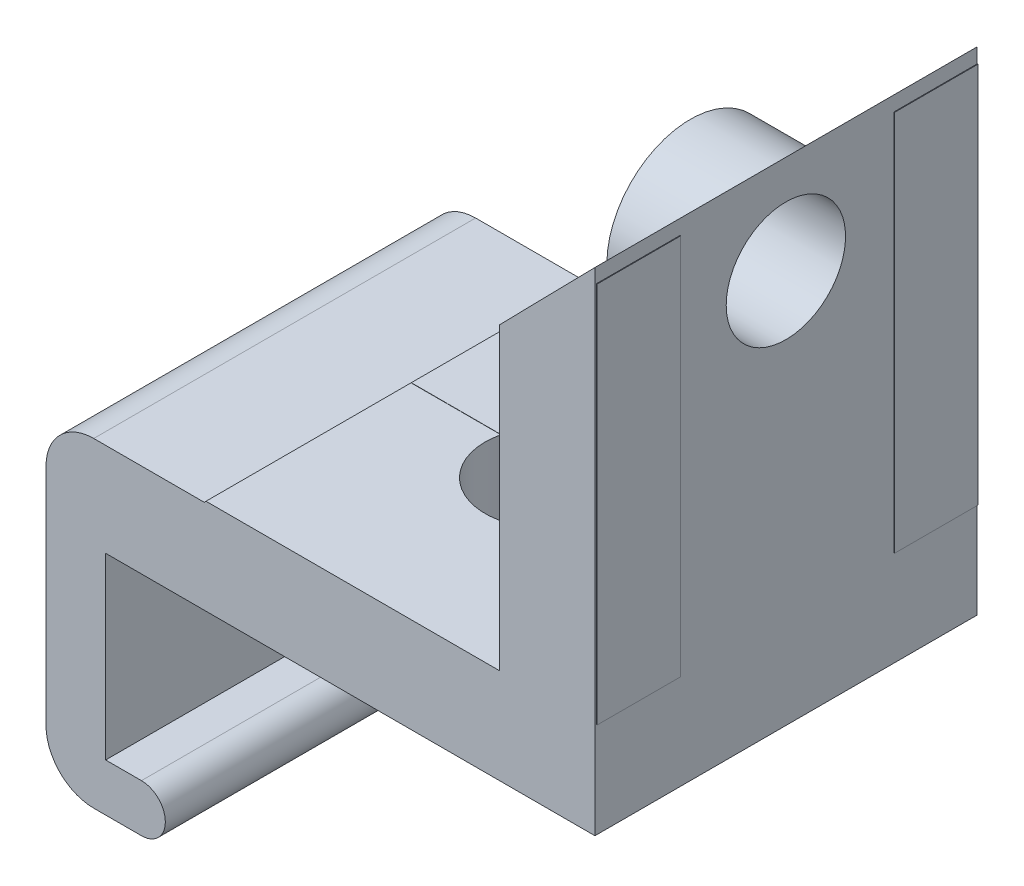
SolidWorks part; units mm, degrees
ref_plane "Front Plane" through (0, 0, 0) normal (0, 0, 1) x (1, 0, 0)
ref_plane "Top Plane" through (0, 0, 0) normal (0, 1, 0) x (1, 0, 0)
ref_plane "Right Plane" through (0, 0, 0) normal (1, 0, 0) x (0, 0, -1)
ref_plane "Plane1" through (16, 0, 0) normal (-1, 0, 0) x (0, -1, 0)
sketch "Sketch1" plane through (16, 0, 0) normal (-1, 0, 0) x (0, -1, 0)
  line L0 (-10.5, 225.9998) -> (-40.6211, 225.9998)
  line L1 (-40.6211, 225.9998) -> (-40.6211, 214.4765)
  line L2 (-40.6211, 214.4765) -> (-10.5, 214.4765)
  line L3 (-10.5, 214.4765) -> (-10.5, 225.9998)
extrude "Boss-Extrude1" add sketch "Sketch1" against normal blind 4
sketch "Sketch2" plane through (20, 0, 0) normal (1, 0, 0) x (0, 0, -1)
  line L0 (-214.5, 24) -> (-214.5, 10.5)
  line L1 (-214.5, 10.5) -> (-214.4765, 10.5)
  line L2 (-214.4765, 10.5) -> (-214.4765, 24)
  line L3 (-214.4765, 24) -> (-214.5, 24)
extrude "Cut-Extrude1" cut sketch "Sketch2" against normal blind 4
sketch "Sketch3" plane through (16, 0, 0) normal (-1, 0, 0) x (0, 0, 1)
  line L0 (225.9998, 10.5) -> (214.5, 10.5)
  line L1 (214.5, 10.5) -> (214.5, 24)
  line L2 (214.5, 24) -> (225.9998, 24)
  line L3 (225.9998, 24) -> (225.9998, 10.5)
extrude "Boss-Extrude2" add sketch "Sketch3" along normal blind 19
sketch "Sketch4" plane through (0, 0, 225.9998) normal (0, 0, 1) x (1, 0, 0)
  line L0 (1, 10.5) -> (20, 10.5)
  line L1 (20, 10.5) -> (20, 12.5)
  line L2 (20, 12.5) -> (1, 12.5)
  arc A0 (1, 12.5) -> (1, 10.5) centre (1, 11.5) cw
extrude "Cut-Extrude2" cut sketch "Sketch4" against normal through all
draft "Draft1" type of draft neutral plane draft angle 45.581 faces to draft 1 face at (18, 40.6211, 220.2382) neutral plane through (20, 0, 0) neutral plane normal (1, 0, 0) reverse direction yes parameters "D1"=45.581
sketch "Sketch5" plane through (-3, 0, 0) normal (-1, 0, 0) x (0, 0, 1)
  line L0 (225.9998, 23.9162) -> (225.9998, 24)
  line L1 (225.9998, 24) -> (214.5, 24)
  line L2 (214.5, 24) -> (214.5, 23.9162)
  line L3 (214.5, 23.9162) -> (225.9998, 23.9162)
extrude "Cut-Extrude3" cut sketch "Sketch5" against normal blind 6.6303
sketch "Sketch6" plane through (0, 12.5, 0) normal (0, -1, 0) x (1, 0, 0)
  line L0 (20, 214.5) -> (20, 225.9998)
  line L1 (20, 225.9998) -> (-0.5, 225.9998)
  line L2 (-0.5, 225.9998) -> (-0.5, 214.5)
  line L3 (-0.5, 214.5) -> (20, 214.5)
extrude "Cut-Extrude4" cut sketch "Sketch6" against normal blind 7.5
sketch "Sketch7" plane through (0, 0, 225.9998) normal (0, 0, 1) x (1, 0, 0)
  line L0 (-3, 10.5) -> (-3, 23.9162)
  line L1 (-3, 23.9162) -> (3.6303, 23.9162)
  line L2 (3.6303, 23.9162) -> (3.6303, 24)
  line L3 (3.6303, 24) -> (16, 24)
  line L4 (16, 24) -> (16, 36.5392)
  line L5 (16, 36.5392) -> (20, 40.6211)
  line L6 (20, 40.6211) -> (20, 20)
  line L7 (20, 20) -> (-0.5, 20)
  line L8 (-0.5, 20) -> (-0.5, 12.5)
  line L9 (-0.5, 12.5) -> (1, 12.5)
  line L10 (1, 10.5) -> (-3, 10.5)
  arc A0 (1, 12.5) -> (1, 10.5) centre (1, 11.5) cw
extrude "Boss-Extrude3" add sketch "Sketch7" along normal blind 4.5002
sketch "Sketch8" plane through (3.6303, 0, 0) normal (-1, 0, 0) x (0, 0, 1)
  line L0 (221.9077, 24) -> (221.9077, 23.9899)
  line L1 (221.9077, 23.9899) -> (230.5, 23.9899)
  line L2 (230.5, 23.9899) -> (230.5, 24)
  line L3 (230.5, 24) -> (221.9077, 24)
extrude "Cut-Extrude5" cut sketch "Sketch8" against normal blind 12.3697
draft "Draft2" type of draft neutral plane draft angle 44.419 faces to draft 1 face at (3.6303, 23.9687, 222.3026) neutral plane through (3.6303, 23.9162, 214.5) neutral plane normal (0, 1, 0) parameters "D1"=44.419
fillet "Fillet1" radius 2 2 edges at (-3, 23.9162, 222.5) (-3, 10.5, 222.5)
ref_plane "Plane2" through (0, 0, 214.5) normal (0, 0, 1) x (1, 0, 0)
sketch "Sketch9" plane through (0, 0, 214.5) normal (0, 0, 1) x (1, 0, 0)
  line L0 (20, 40) -> (20, 40.6211)
  line L1 (20, 40.6211) -> (19.3913, 40)
  line L2 (19.3913, 40) -> (20, 40)
extrude "Cut-Extrude6" cut sketch "Sketch9" against normal up to next
ref_plane "Plane3" through (20.0268, 0, 0) normal (1, 0, 0) x (0, 0, -1)
sketch "Sketch10" plane through (20.0268, 0, 0) normal (1, 0, 0) x (0, 0, -1)
  line L0 (-217.9765, 24) -> (-214.4765, 24)
  line L1 (-214.4765, 24) -> (-214.4765, 40)
  line L2 (-214.4765, 40) -> (-217.9765, 40)
  line L3 (-217.9765, 40) -> (-217.9765, 24)
extrude "Boss-Extrude4" add sketch "Sketch10" against normal up to surface (0.0268 mm away) up to face at (20, 31.1553, 218.4941)
sketch "Sketch11" plane through (20.0268, 0, 0) normal (1, 0, 0) x (0, 0, -1)
  line L0 (-230.4332, 24) -> (-226.9332, 24)
  line L1 (-226.9332, 24) -> (-226.9332, 40)
  line L2 (-226.9332, 40) -> (-230.4332, 40)
  line L3 (-230.4332, 40) -> (-230.4332, 24)
extrude "Boss-Extrude5" add sketch "Sketch11" against normal up to surface (0.0268 mm away) up to face at (20, 31.3665, 219.3691)
ref_plane "Plane4" through (0, 0, 214.4765) normal (0, 0, -1) x (-1, 0, 0)
sketch "Sketch12" plane through (0, 0, 214.4765) normal (0, 0, -1) x (-1, 0, 0)
  line L0 (-16, 24) -> (-3.7124, 24)
  line L1 (-3.7124, 24) -> (-16, 36.5392)
  line L2 (-16, 36.5392) -> (-16, 24)
extrude "Boss-Extrude6" add sketch "Sketch12" against normal blind 3.5
hole_wizard "Ø5.2 (5.2) Diameter Hole1" positions "Sketch14" profile "Sketch13" hole size "Ø5.2" standard "ANSI Metric"
sketch "Sketch14" plane through (0, 20, 0) normal (0, -1, 0) x (-1, 0, 0)
  point P0 (-10, -222.5)
sketch "Sketch13" plane through (10, 20, 222.5) normal (1, 0, 0) x (0, 0, -1)
  line L0 (0, 0) -> (0, 20.6212)
  line L1 (0, 20.6212) -> (2.6, 20.6212)
  line L2 (2.6, 20.6212) -> (2.6, 0)
  line L5 (2.6, 0) -> (0, 0)
  line L11 (0, -6.35) -> (0, 107.95) construction
  dimension "Thru Hole Dia." = 5.2
  dimension "Thru Hole Depth" = 20.6212
hole_wizard "Ø5.0 (5) Diameter Hole1" positions "Sketch16" profile "Sketch15" hole size "Ø5.0" standard "ANSI Metric"
sketch "Sketch16" plane through (16, 0, 0) normal (-1, 0, 0) x (0, 0, 1)
  point P0 (222.5, 36.5)
sketch "Sketch15" plane through (16, 36.5, 222.5) normal (0, 1, 0) x (0, 0, 1)
  line L0 (0, 0) -> (0, 4.0268)
  line L1 (0, 4.0268) -> (2.5, 4.0268)
  line L2 (2.5, 4.0268) -> (2.5, 0)
  line L5 (2.5, 0) -> (0, 0)
  line L11 (0, -6.35) -> (0, 107.95) construction
  dimension "Thru Hole Dia." = 5
  dimension "Thru Hole Depth" = 4.0268
ref_point "Point1"
sketch "Sketch17" plane through (16, 0, 0) normal (-1, 0, 0) x (0, 0, 1)
  circle A0 centre (222.5, 36.5) radius 3.5
  circle A1 centre (222.5, 36.5) radius 2.5 construction
  circle A2 centre (222.5, 36.5) radius 2.5
extrude "Boss-Extrude7" add sketch "Sketch17" against normal up to surface (4 mm away) up to face at (20, 36.5, 225)
